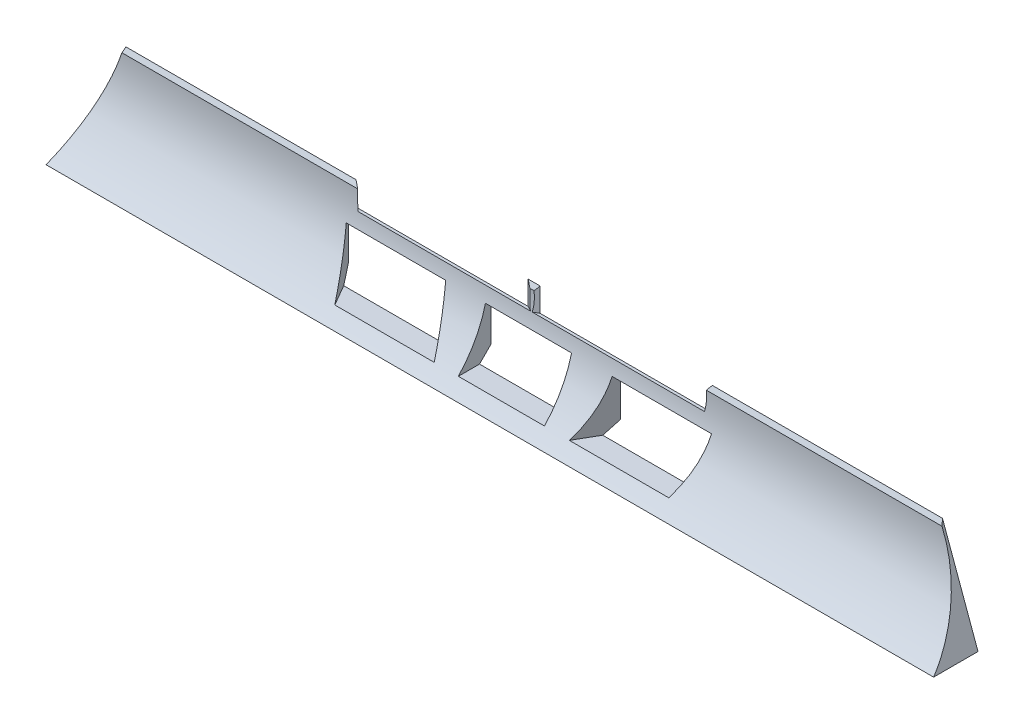
SolidWorks part; units mm, degrees
material "ABS"
ref_plane "Front Plane" through (0, 0, 0) normal (0, 0, 1) x (1, 0, 0)
ref_plane "Top Plane" through (0, 0, 0) normal (0, 1, 0) x (1, 0, 0)
ref_plane "Right Plane" through (0, 0, 0) normal (1, 0, 0) x (0, 0, -1)
sketch "Sketch1" plane through (0, 0, 0) normal (1, 0, 0) x (0, 0, -1)
  line L0 (0, 0) -> (-10, 0)
  line L1 (-10, 0) -> (0, 22)
  line L2 (0, 22) -> (0, 0)
  dimension "D1" = 10
  dimension "D2" = 22
extrude "Boss-Extrude1" add sketch "Sketch1" along normal blind 200
sketch "Sketch2" plane through (200, 0, 0) normal (1, 0, 0) x (0, 0, -1)
  line L0 (0, 22) -> (-10, 0) construction
  line L1 (-10, 0) -> (0, 0) construction
  line L2 (0, 0) -> (0, 22) construction
  line L3 (-10, 0) -> (-0.5, 20.9)
  arc A0 (-10, 0) -> (-0.5, 20.9) centre (-25.4682, 19.6401) ccw
  dimension "D3" = 25
  dimension "D1" = 0
  dimension "D2" = 0.5
extrude "Cut-Extrude1" cut sketch "Sketch2" against normal through all
sketch "Sketch4" plane through (200, 0, 0) normal (1, 0, 0) x (0, 0, -1)
  line L0 (-5, 0) -> (0, 5)
  line L1 (-10, 0) -> (0, 0) construction
  line L2 (0, 0) -> (0, 22) construction
  line L3 (0, 5) -> (0, 0)
  line L4 (0, 0) -> (-5, 0)
  dimension "D1" = 5
  dimension "D2" = 5
extrude "Cut-Extrude2" cut sketch "Sketch4" against normal through all
sketch "Sketch5" plane through (0, 0, 0) normal (0, 0, -1) x (-1, 0, 0)
  line L0 (0, 0) -> (-200, 0) construction
  line L1 (-200, 5) -> (-197, 5)
  line L2 (-200, 5) -> (-200, 0)
  line L3 (-200, 0) -> (-197, 0)
  line L4 (-197, 5) -> (-197, 0)
  dimension "D1" = 3
extrude "Boss-Extrude2" add sketch "Sketch5" against normal up to surface up to face at (100, 2.5, 2.5)
ref_plane "Plane1" through (100, 0, 0) normal (1, 0, 0) x (0, 0, -1)
sketch "Sketch6" plane through (0, 0, 0) normal (0, 0, -1) x (-1, 0, 0)
  line L0 (-200, 22) -> (-191.9927, 22)
  line L1 (-200, 22) -> (0, 22) construction
  line L2 (-191.9927, 22) -> (-200, 0)
  line L3 (-200, 22) -> (-200, 0)
  dimension "D1" = 20
extrude "Cut-Extrude3" cut sketch "Sketch6" against normal through all
mirror "Mirror2" about plane through (100, 0, 0) normal (1, 0, 0) of "Cut-Extrude3", "Boss-Extrude2"
sketch "Sketch8" plane through (0, 0, 0) normal (0, 0, -1) x (-1, 0, 0)
  line L1 (-165.6214, 11.1) -> (-167.4112, 8)
  line L2 (-167.4112, 8) -> (-165.6214, 4.9)
  line L3 (-165.6214, 4.9) -> (-162.0418, 4.9)
  line L4 (-162.0418, 4.9) -> (-160.252, 8)
  line L5 (-160.252, 8) -> (-162.0418, 11.1)
  line L6 (-162.0418, 11.1) -> (-165.6214, 11.1)
  line L7 (-167.8316, 0) -> (-159.8316, 0) construction
  line L8 (-165.3316, 10.465) -> (-165.3316, 5.465) construction
  circle A2 centre (-163.8316, 8) radius 3.1 construction
  point P13 (-163.8316, 11.1)
  dimension "D1" = 6.2
  dimension "D2" = 1.5
  dimension "D3" = 8
extrude "Cut-Extrude4" cut sketch "Sketch8" against normal blind 1.8 contours L5 L6 L1 L2 L3 L4
sketch "Sketch9" plane through (0, 0, 0) normal (0, 0, 1) x (1, 0, 0)
  line L1 (92.2158, 4.465) -> (107.6158, 4.465)
  line L2 (92.2158, 4.465) -> (92.2158, 11.665)
  line L3 (92.2158, 11.665) -> (107.6158, 11.665)
  line L4 (107.6158, 4.465) -> (107.6158, 11.665)
  line L8 (90.2158, 13.665) -> (109.6158, 13.665)
  line L9 (109.6158, 2.465) -> (109.6158, 13.665)
  line L10 (90.2158, 2.465) -> (109.6158, 2.465)
  line L11 (90.2158, 2.465) -> (90.2158, 13.665)
  dimension "D1" = 2
extrude "Cut-Extrude6" cut sketch "Sketch9" along normal through all contours L11 L10 L9 L8 L4 L1 L2 L3
ref_plane "Plane2" through (32.136, 0, -55.6612) normal (-0.5, 0, 0.866) x (0.866, 0, 0.5)
sketch "Sketch10" plane through (32.136, 0, -55.6612) normal (-0.5, 0, 0.866) x (0.866, 0, 0.5)
  line L0 (103.439, 13.665) -> (122.839, 13.665)
  line L1 (105.439, 4.465) -> (120.839, 4.465)
  line L2 (105.439, 4.465) -> (105.439, 11.665)
  line L3 (105.439, 11.665) -> (120.839, 11.665)
  line L4 (120.839, 4.465) -> (120.839, 11.665)
  line L5 (122.839, 2.465) -> (122.839, 13.665)
  line L6 (103.439, 2.465) -> (122.839, 2.465)
  line L7 (103.439, 2.465) -> (103.439, 13.665)
  dimension "D1" = 2
extrude "Cut-Extrude8" cut sketch "Sketch10" along normal blind 15.8 and the other way blind 6.8 contours L1 L4 L3 L2 | L7 L6 L5 L0 L4 L1 L2 L3
ref_plane "Plane3" through (115.6697, 0, -66.7819) normal (-0.866, 0, 0.5) x (0.5, 0, 0.866)
sketch "Sketch11" plane through (115.6697, 0, -66.7819) normal (-0.866, 0, 0.5) x (0.5, 0, 0.866)
  line L0 (70.0717, 29.465) -> (70.0717, 16.665)
  line L1 (68.0717, 27.465) -> (52.6717, 27.465)
  line L2 (68.0717, 27.465) -> (68.0717, 18.665)
  line L3 (68.0717, 18.665) -> (52.6717, 18.665)
  line L4 (52.6717, 27.465) -> (52.6717, 18.665)
  line L5 (70.0717, 16.665) -> (50.6717, 16.665)
  line L6 (50.6717, 29.465) -> (50.6717, 16.665)
  line L7 (52.6717, 27.465) -> (52.6717, 20.265) construction
  line L8 (47.1217, 18.665) -> (73.6217, 18.665) construction
  line L9 (70.0717, 29.465) -> (50.6717, 29.465)
  dimension "D1" = 2
extrude "Cut-Extrude9" cut sketch "Sketch11" along normal blind 97.8 contours L1 L4 L3 L2 | L0 L9 L6 L5 L4 L1 L2 L3
mirror "Mirror4" about plane through (100, 0, 0) normal (1, 0, 0) of "Cut-Extrude8", "Cut-Extrude9"
mirror "Mirror5" about plane through (100, 0, 0) normal (1, 0, 0) of "Cut-Extrude4"
